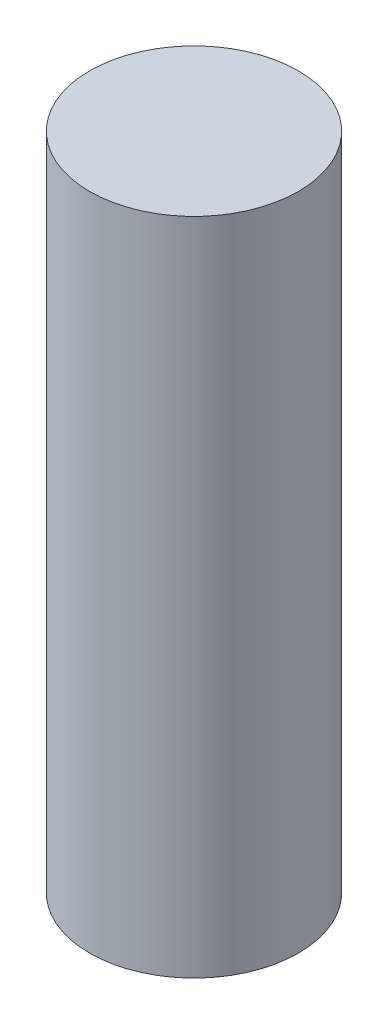
SolidWorks part; units mm, degrees
material "Custom Plastic"
ref_plane "Front Plane" through (0, 0, 0) normal (0, 0, 1) x (1, 0, 0)
ref_plane "Top Plane" through (0, 0, 0) normal (0, 1, 0) x (1, 0, 0)
ref_plane "Right Plane" through (0, 0, 0) normal (1, 0, 0) x (0, 0, -1)
sketch "Sketch1" plane through (0, 0, 0) normal (0, 1, 0) x (1, 0, 0)
  circle A0 centre (0, 0) radius 1.425
  dimension "D1" = 2.85
extrude "Boss-Extrude1" add sketch "Sketch1" along normal blind 9
